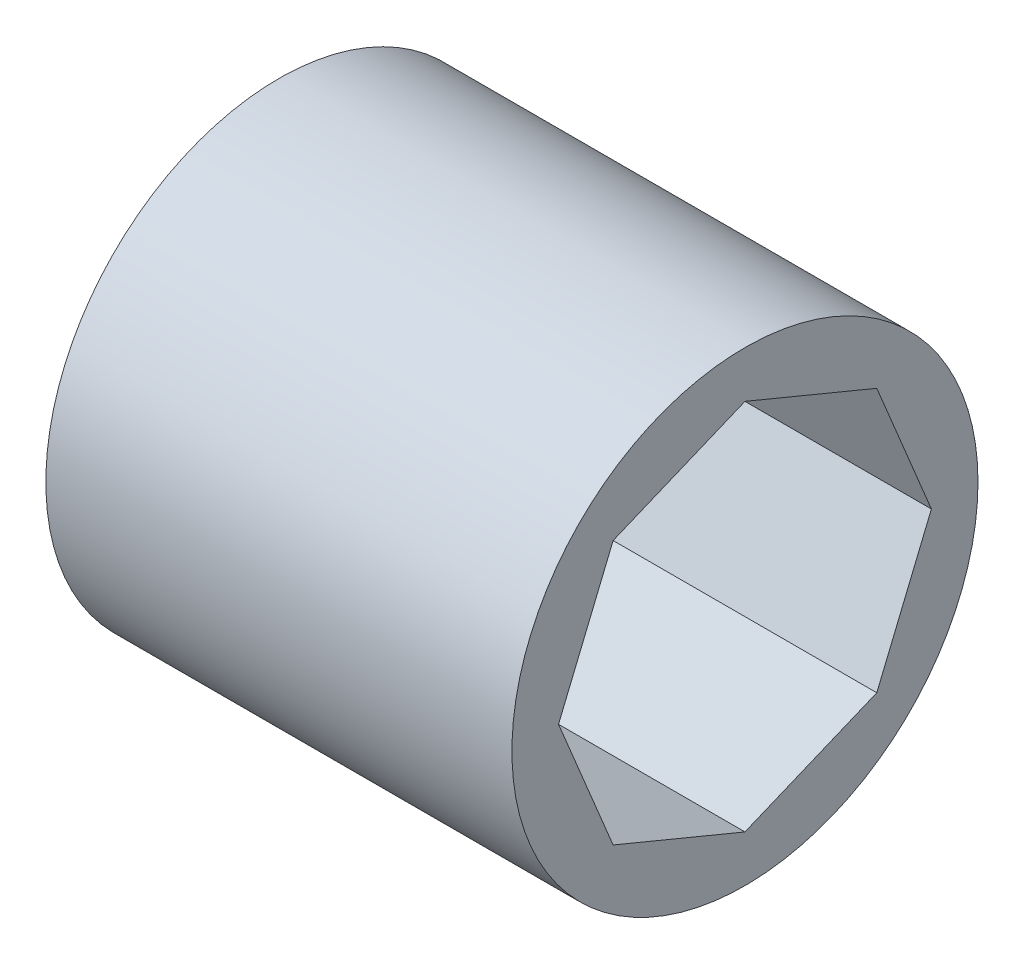
SolidWorks part; units mm, degrees
ref_plane "Front Plane" through (0, 0, 0) normal (0, 0, 1) x (1, 0, 0)
ref_plane "Top Plane" through (0, 0, 0) normal (0, 1, 0) x (1, 0, 0)
ref_plane "Right Plane" through (0, 0, 0) normal (1, 0, 0) x (0, 0, -1)
sketch "Sketch2" plane through (0, 0, 0) normal (1, 0, 0) x (0, 0, -1)
  circle A0 centre (0, 0) radius 10
  dimension "D1" = 20
extrude "Boss-Extrude5" add sketch "Sketch2" along normal blind 20
sketch "Sketch5" plane through (20, 0, 0) normal (1, 0, 0) x (0, 0, -1)
  line L1 (8, 0) -> (5.6569, 5.6569)
  line L2 (5.6569, 5.6569) -> (0, 8)
  line L3 (0, 8) -> (-5.6569, 5.6569)
  line L4 (-5.6569, 5.6569) -> (-8, 0)
  line L5 (-8, 0) -> (-5.6569, -5.6569)
  line L6 (-5.6569, -5.6569) -> (0, -8)
  line L7 (0, -8) -> (5.6569, -5.6569)
  line L8 (5.6569, -5.6569) -> (8, 0)
  circle A0 centre (0, 0) radius 7.391 construction
  dimension "D1" = 8
extrude "Cut-Extrude1" cut sketch "Sketch5" against normal blind 20
